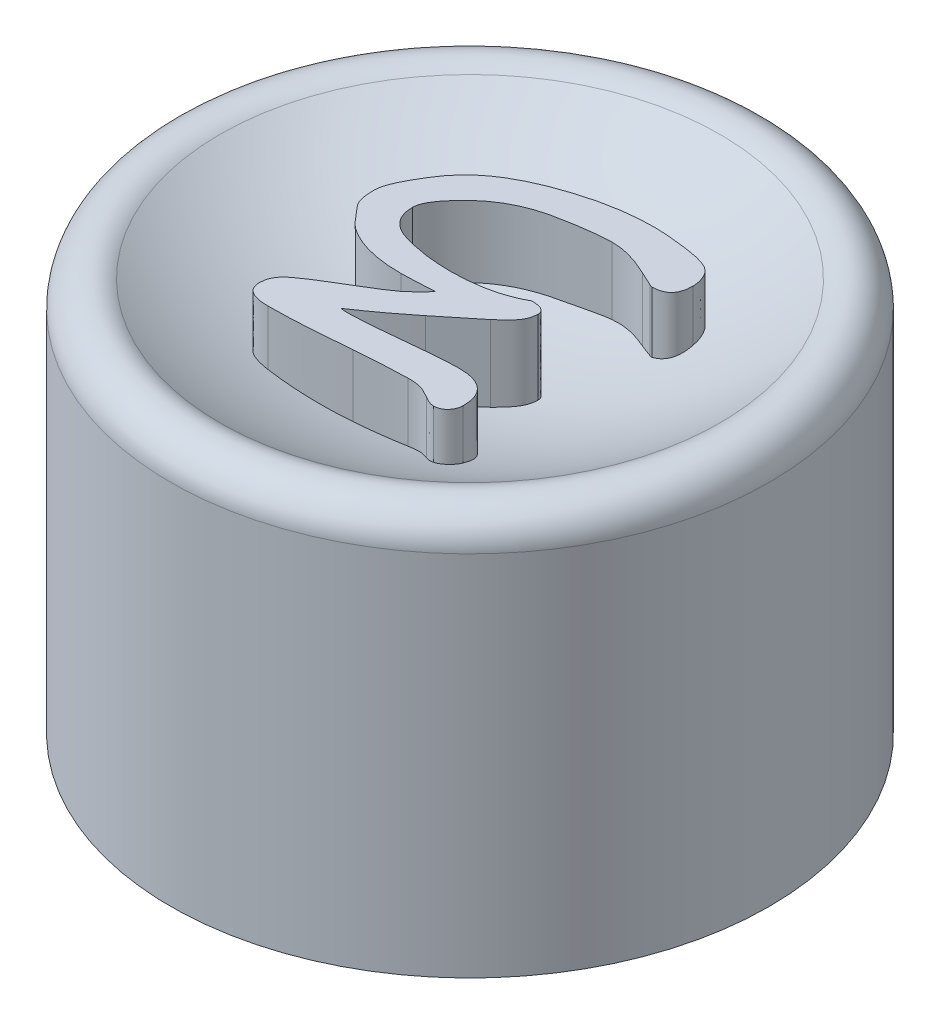
SolidWorks part; units mm, degrees
ref_plane "Front Plane" through (0, 0, 0) normal (0, 0, 1) x (1, 0, 0)
ref_plane "Top Plane" through (0, 0, 0) normal (0, 1, 0) x (1, 0, 0)
ref_plane "Right Plane" through (0, 0, 0) normal (1, 0, 0) x (0, 0, -1)
sketch "Sketch1" plane through (0, 0, 0) normal (0, 0, 1) x (1, 0, 0)
  line L0 (0, 0) -> (0, -66.4851) construction
  line L1 (55, 0) -> (-55, 0) construction
  line L2 (-1.5494, 0) -> (-1.5494, 3.048)
  line L3 (-1.5494, 3.048) -> (-0.762, 3.048)
  line L4 (-0.762, 3.048) -> (-0.762, 4.064)
  line L5 (-0.762, 4.064) -> (0, 4.064)
  line L6 (0, -55) -> (0, 55) construction
  line L7 (0, 4.064) -> (0, 5.08)
  line L8 (-4.7625, 5.842) -> (-4.7625, 0)
  line L9 (-4.7625, 0) -> (-3.4925, 0)
  line L10 (-3.4925, 0) -> (-3.4925, 4.064)
  line L11 (-3.4925, 4.064) -> (-2.0574, 4.064)
  line L12 (-2.0574, 4.064) -> (-2.0574, 0)
  line L13 (-2.0574, 0) -> (-1.5494, 0)
  line L14 (0, 5.08) -> (3.3062, 5.08) construction
  arc A0 (-4.7625, 5.842) -> (-3.976, 6.2669) centre (-4.2545, 5.842) cw
  arc A1 (-3.976, 6.2669) -> (0, 5.08) centre (0, 12.3333) ccw
  dimension "D4" = 1.524
  dimension "D5" = 6.35
  dimension "D9" = 0.508
  dimension "D1" = 9.525
  dimension "D2" = 3.0988
  dimension "D3" = 3.048
  dimension "D6" = 0.508
  dimension "D7" = 1.016
  dimension "D8" = 1.27
  dimension "D10" = 5.08
revolve "Revolve1" add sketch "Sketch1" angle 360 about L0
ref_plane "Plane1" through (0, 6.35, 0) normal (0, 1, 0) x (-1, 0, 0)
sketch "Sketch3" plane through (0, 6.35, 0) normal (0, 1, 0) x (-1, 0, 0)
  line L0 (-2.3812, -2.032) -> (2.3813, -2.032) construction
  line L1 (0, 0) -> (0, -7.9672) construction
  line L2 (0, 3.4925) -> (0, -3.4925) construction
  line L3 (3.4925, 0) -> (-3.4925, 0) construction
  text T0 "3" font "Segoe Print" height 4.7625
  dimension "D1" = 2.032
  dimension "D2" = 4.7625
extrude "Boss-Extrude1" add sketch "Sketch3" against normal up to surface (1.1282 mm away)
